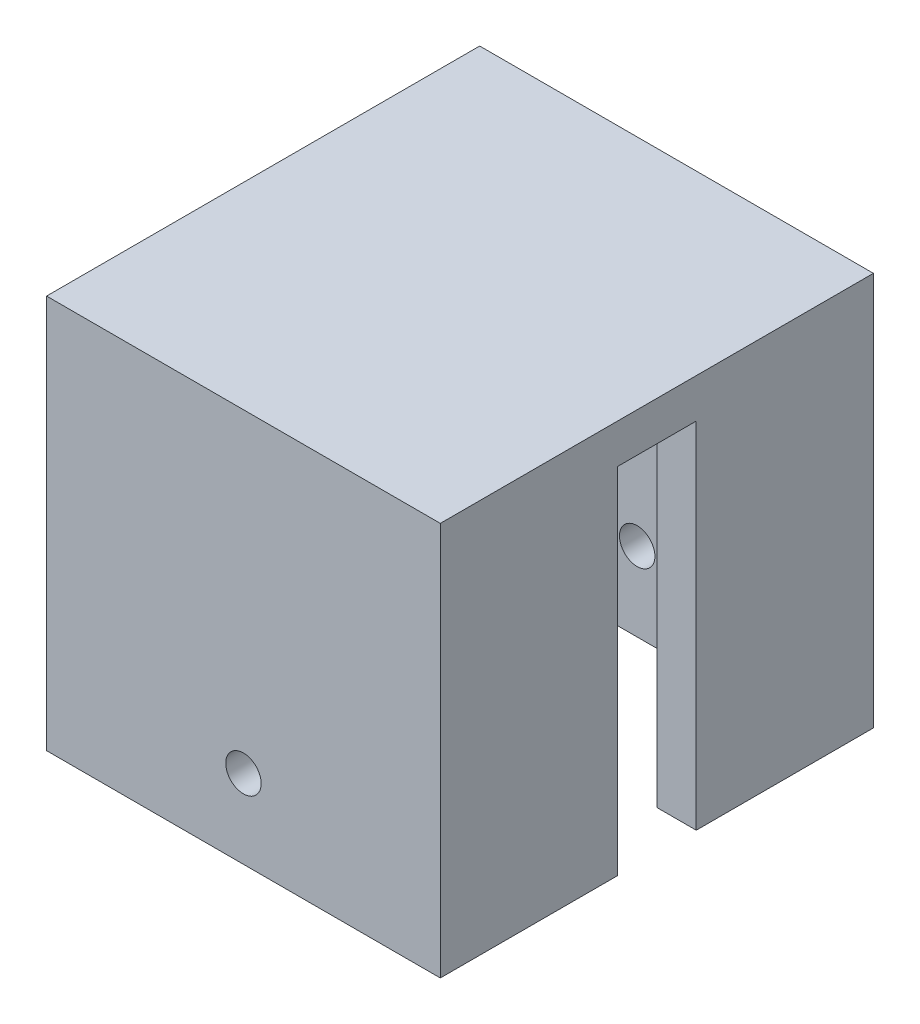
SolidWorks part; units mm, degrees
material "Papel canelado"
ref_plane "Plano frontal" through (0, 0, 0) normal (0, 0, 1) x (1, 0, 0)
ref_plane "Plano superior" through (0, 0, 0) normal (0, 1, 0) x (1, 0, 0)
ref_plane "Plano direito" through (0, 0, 0) normal (1, 0, 0) x (0, 0, -1)
sketch "Esboço1" plane through (0, 0, 0) normal (0, 0, 1) x (1, 0, 0)
  line L1 (0, 0) -> (50, 0)
  line L2 (0, 0) -> (0, 50)
  line L3 (0, 50) -> (50, 50)
  line L4 (50, 0) -> (50, 50)
  dimension "D1" = 50
  dimension "D2" = 50
extrude "Ressalto-extrusão1" add sketch "Esboço1" along normal blind 55
shell "Casca2" thickness 5
sketch "Esboço2" plane through (0, 0, 55) normal (0, 0, 1) x (1, 0, 0)
  line L0 (0, 0) -> (50, 0) construction
  line L1 (50, 50) -> (0, 50) construction
  line L3 (25, -988.1607) -> (25, 48923.4135) construction
  circle A0 centre (25, 10) radius 2.25
  point P5 (28.2024, 10)
  point P7 (25, 50)
  point P8 (27.3848, 10)
  dimension "D1" = 10
  dimension "D2" = 4.5
extrude "Corte-extrusão1" cut sketch "Esboço2" against normal through all
sketch "Esboço3" plane through (50, 0, 0) normal (1, 0, 0) x (0, 0, -1)
  line L0 (-55, 0) -> (0, 0) construction
  line L1 (-32.5, 0) -> (-22.5, 0)
  line L2 (-32.5, 0) -> (-32.5, 45)
  line L3 (-32.5, 45) -> (-22.5, 45)
  line L4 (-22.5, 0) -> (-22.5, 45)
  line L5 (-55, 50) -> (0, 50) construction
  point P8 (-44.9428, 45)
  point P9 (-27.5, 0)
  point P10 (-27.5, 0)
  dimension "D1" = 10
  dimension "D2" = 5
extrude "Corte-extrusão2" cut sketch "Esboço3" against normal through all
